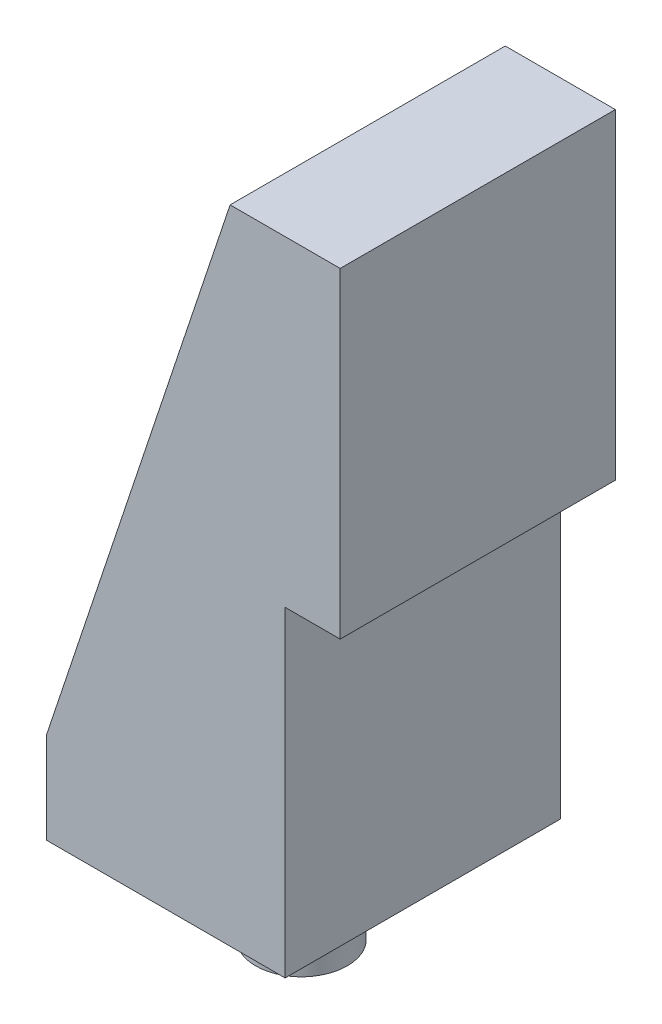
SolidWorks part; units mm, degrees
ref_plane "Front Plane" through (0, 0, 0) normal (0, 0, 1) x (1, 0, 0)
ref_plane "Top Plane" through (0, 0, 0) normal (0, 1, 0) x (1, 0, 0)
ref_plane "Right Plane" through (0, 0, 0) normal (1, 0, 0) x (0, 0, -1)
sketch "Sketch1" plane through (0, 0, 0) normal (0, 0, 1) x (1, 0, 0)
  line L0 (0, 0) -> (1.3, 0)
  line L1 (1.3, 0) -> (1.3, 1.75)
  line L2 (1.3, 3.5) -> (1, 3.5)
  line L3 (1, 3.5) -> (0, 0.5)
  line L4 (0, 0.5) -> (0, 0)
  line L5 (1.3, 3.5) -> (1.6, 3.5)
  line L6 (1.6, 3.5) -> (1.6, 1.75)
  line L7 (1.6, 1.75) -> (1.3, 1.75)
  dimension "D1" = 1.3
  dimension "D2" = 3.5
  dimension "D3" = 0.3
  dimension "D4" = 0.5
  dimension "D5" = 0.3
extrude "Boss-Extrude1" add sketch "Sketch1" along normal blind 1.5
sketch "Sketch2" plane through (0, 0, 0) normal (0, -1, 0) x (1, 0, 0)
  circle A0 centre (0.6623, 0.7733) radius 0.25
  dimension "D1" = 0.5
extrude "Boss-Extrude2" add sketch "Sketch2" along normal blind 0.5
